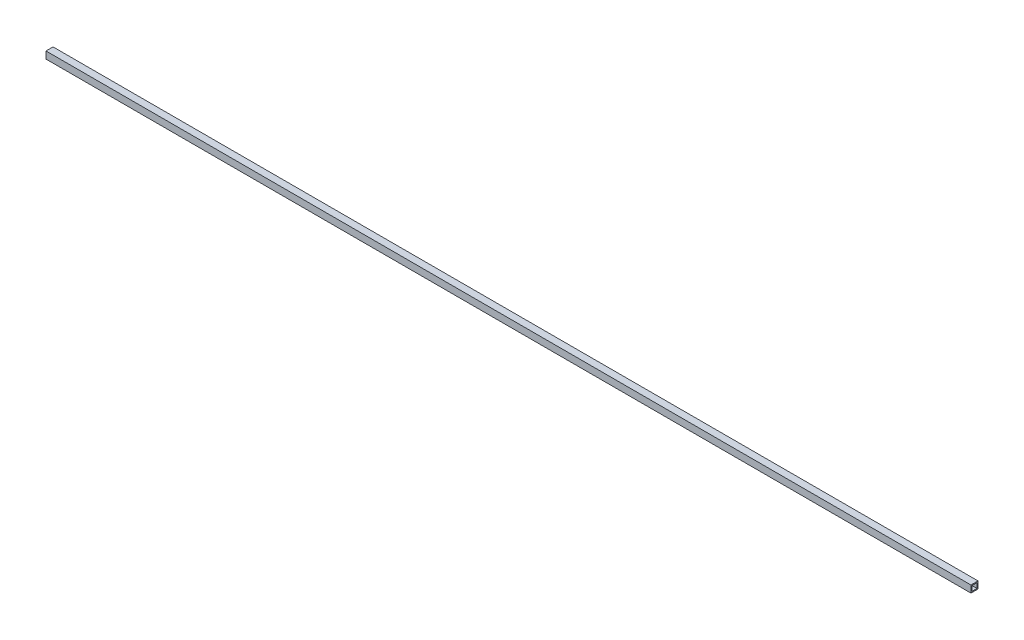
SolidWorks part; units mm, degrees
ref_plane "Front Plane" through (0, 0, 0) normal (0, 0, 1) x (1, 0, 0)
ref_plane "Top Plane" through (0, 0, 0) normal (0, 1, 0) x (1, 0, 0)
ref_plane "Right Plane" through (0, 0, 0) normal (1, 0, 0) x (0, 0, -1)
sketch "Sketch1" plane through (0, 0, 0) normal (0, 1, 0) x (1, 0, 0)
  line L1 (0, 0) -> (1310, 0)
  line L2 (0, 0) -> (0, -10)
  line L3 (0, -10) -> (1310, -10)
  line L4 (1310, 0) -> (1310, -10)
  dimension "D1" = 10
  dimension "D2" = 1310
extrude "Boss-Extrude1" add sketch "Sketch1" along normal blind 10 contours L3 L4 L1 L2
sketch "Sketch2" plane through (1310, 0, 0) normal (1, 0, 0) x (0, 0, -1)
  line L0 (0, 10) -> (-10, 10) construction
  line L1 (-1.5, 8.5) -> (-8.5, 8.5)
  line L2 (-1.5, 8.5) -> (-1.5, 1.5)
  line L3 (-1.5, 1.5) -> (-8.5, 1.5)
  line L4 (-8.5, 8.5) -> (-8.5, 1.5)
  line L5 (0, 10) -> (0, 0) construction
  line L6 (0, 0) -> (-10, 0) construction
  line L7 (-10, 10) -> (-10, 0) construction
  dimension "D1" = 1.5
  dimension "D2" = 1.5
  dimension "D3" = 1.5
  dimension "D4" = 1.5
extrude "Cut-Extrude1" cut sketch "Sketch2" against normal through all
equation "\"D2@Sketch2\"=\"D1@Sketch2\""
equation "\"D3@Sketch2\"=\"D2@Sketch2\""
equation "\"D4@Sketch2\"=\"D1@Sketch2\""
